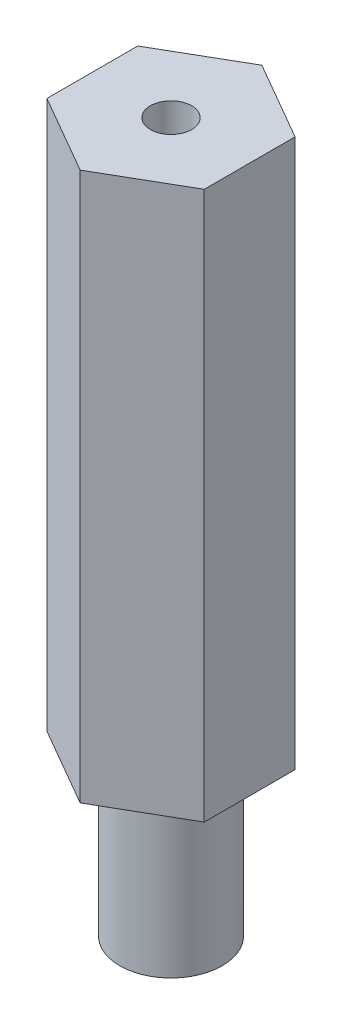
SolidWorks part; units mm, degrees
material "6061-T6 (SS)"
ref_plane "Front Plane" through (0, 0, 0) normal (0, 0, 1) x (1, 0, 0)
ref_plane "Top Plane" through (0, 0, 0) normal (0, 1, 0) x (1, 0, 0)
ref_plane "Right Plane" through (0, 0, 0) normal (1, 0, 0) x (0, 0, -1)
sketch "Sketch1" plane through (0, 0, 0) normal (0, 1, 0) x (1, 0, 0)
  line L1 (2.2606, 1.3052) -> (0, 2.6103)
  line L2 (0, 2.6103) -> (-2.2606, 1.3052)
  line L3 (-2.2606, 1.3052) -> (-2.2606, -1.3052)
  line L4 (-2.2606, -1.3052) -> (0, -2.6103)
  line L5 (0, -2.6103) -> (2.2606, -1.3052)
  line L6 (2.2606, -1.3052) -> (2.2606, 1.3052)
  circle A0 centre (0, 0) radius 2.2606 construction
  dimension "D1" = 4.5212
extrude "Boss-Extrude1" add sketch "Sketch1" along normal blind 15.748
sketch "Sketch2" plane through (0, 0, 0) normal (0, -1, 0) x (1, 0, 0)
  circle A0 centre (0, 0) radius 1.4732
  dimension "D1" = 2.9464
extrude "Boss-Extrude2" add sketch "Sketch2" along normal blind 4.6228
sketch "Sketch3" plane through (0, 15.748, 0) normal (0, 1, 0) x (1, 0, 0)
  circle A0 centre (0, 0) radius 0.5937
extrude "Cut-Extrude1" cut sketch "Sketch3" against normal blind 2.54
